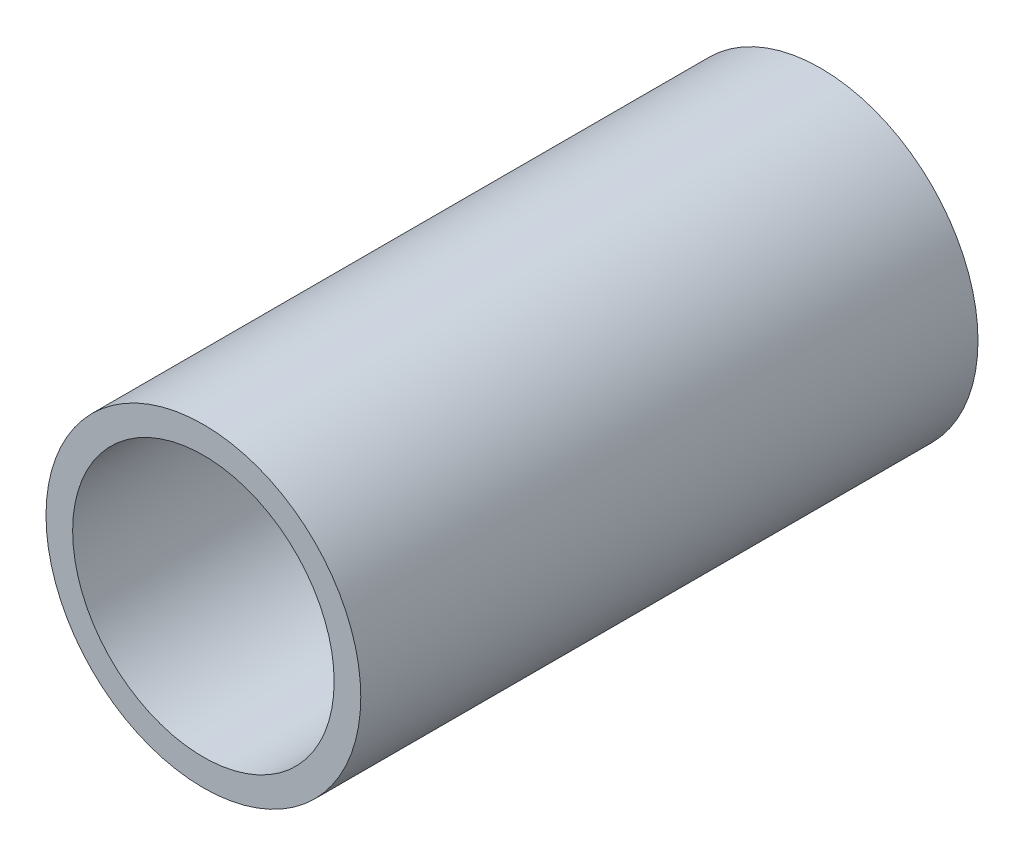
SolidWorks part; units mm, degrees
ref_plane "Front Plane" through (0, 0, 0) normal (0, 0, 1) x (1, 0, 0)
ref_plane "Top Plane" through (0, 0, 0) normal (0, 1, 0) x (1, 0, 0)
ref_plane "Right Plane" through (0, 0, 0) normal (1, 0, 0) x (0, 0, -1)
sketch "Sketch1" plane through (0, 0, 0) normal (0, 0, 1) x (1, 0, 0)
  circle A0 centre (0, 0) radius 12.5
  dimension "D1" = 25
extrude "Boss-Extrude1" add sketch "Sketch1" along normal blind 49.02
sketch "Sketch2" plane through (0, 0, 0) normal (0, 0, -1) x (-1, 0, 0)
  circle A0 centre (0, 0) radius 10.385
  dimension "D1" = 20.77
extrude "Cut-Extrude1" cut sketch "Sketch2" against normal through all
